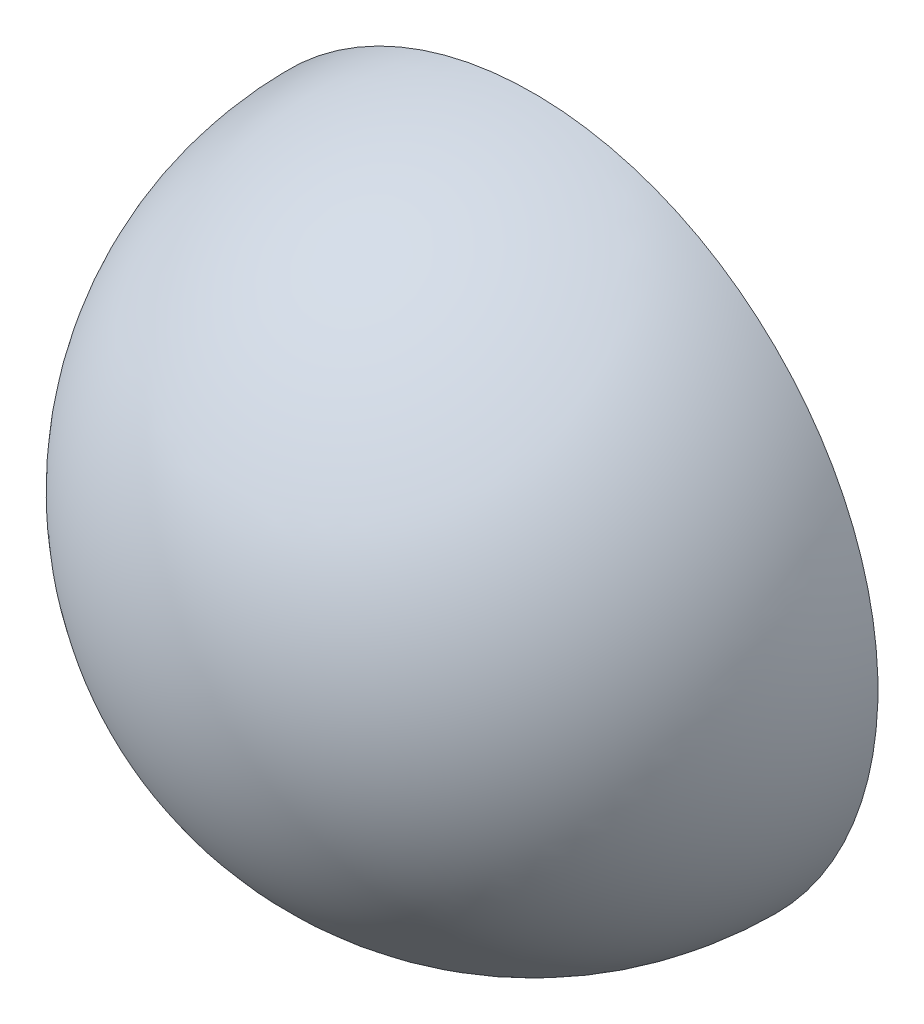
SolidWorks part; units mm, degrees
material "丙烯酸(中高冲击)"
ref_plane "前视基准面" through (0, 0, 0) normal (0, 0, 1) x (1, 0, 0)
ref_plane "上视基准面" through (0, 0, 0) normal (0, 1, 0) x (1, 0, 0)
ref_plane "右视基准面" through (0, 0, 0) normal (1, 0, 0) x (0, 0, -1)
sketch "草图1" plane through (0, 0, 0) normal (0, 0, 1) x (1, 0, 0)
  line L0 (0, 60) -> (0, 58)
  line L1 (0, -58) -> (0, -60)
  arc A0 (0, -60) -> (0, 60) centre (0, 0) ccw
  arc A1 (0, -58) -> (0, 58) centre (0, 0) ccw
  dimension "D1" = 120
  dimension "D2" = 2
revolve "旋转3" add sketch "草图1" angle 180 about L0
